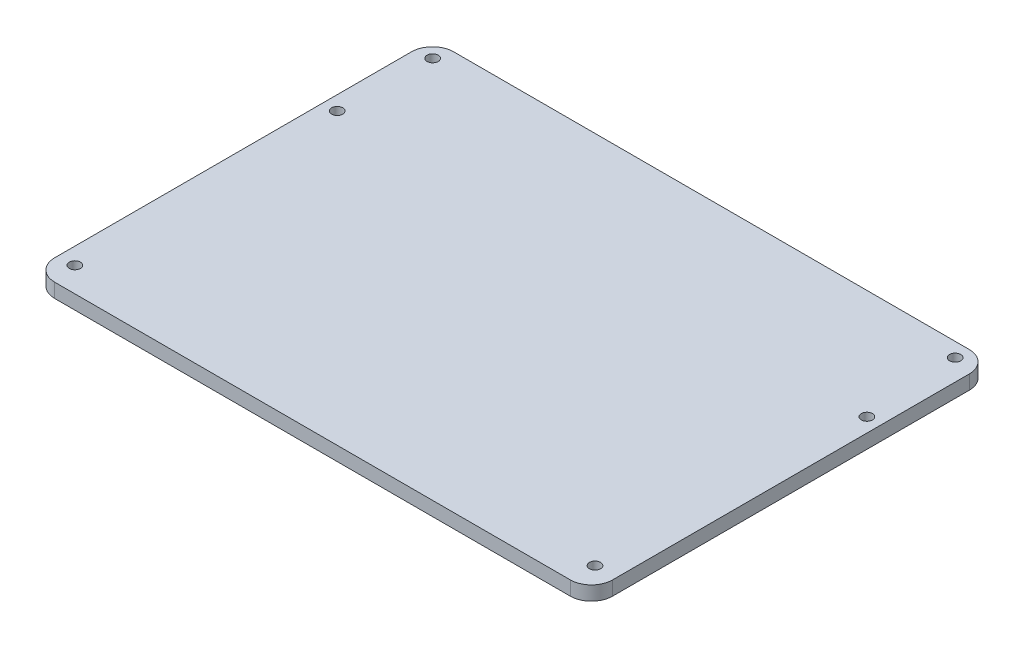
SolidWorks part; units mm, degrees
material "Thornel Mat VMA"
ref_plane "Front Plane" through (0, 0, 0) normal (0, 0, 1) x (1, 0, 0)
ref_plane "Top Plane" through (0, 0, 0) normal (0, 1, 0) x (1, 0, 0)
ref_plane "Right Plane" through (0, 0, 0) normal (1, 0, 0) x (0, 0, -1)
sketch "Sketch1" plane through (0, 0, 0) normal (0, 1, 0) x (1, 0, 0)
  line L0 (-75.9923, 25.544) -> (109.4277, 25.544)
  line L1 (-83.6123, 17.924) -> (-83.6123, -110.346)
  line L2 (117.0477, 17.924) -> (117.0477, -110.346)
  line L3 (-75.9923, -117.966) -> (109.4277, -117.966)
  arc A0 (-83.6123, -110.346) -> (-75.9923, -117.966) centre (-75.9923, -110.346) ccw
  arc A1 (117.0477, -110.346) -> (109.4277, -117.966) centre (109.4277, -110.346) cw
  arc A2 (109.4277, 25.544) -> (117.0477, 17.924) centre (109.4277, 17.924) cw
  arc A3 (-83.6123, 17.924) -> (-75.9923, 25.544) centre (-75.9923, 17.924) cw
  point P7 (-83.6123, -117.966)
  point P12 (117.0477, 25.544)
  point P15 (-83.6123, 25.544)
  dimension "D3" = 7.62
  dimension "D1" = 143.51
  dimension "D2" = 200.66
extrude "Boss-Extrude1" add sketch "Sketch1" along normal blind 5.08
sketch "Sketch2" plane through (0, 5.08, 0) normal (0, 1, 0) x (1, 0, 0)
  line L0 (-83.6123, 17.924) -> (-83.6123, -110.346) construction
  line L1 (-75.9923, -117.966) -> (109.4277, -117.966) construction
  line L2 (117.0477, -110.346) -> (117.0477, 17.924) construction
  line L4 (109.4277, 25.544) -> (-75.9923, 25.544) construction
  line L5 (104.3477, 20.464) -> (-70.9123, 20.464) construction
  line L6 (16.7177, 25.544) -> (16.7177, 87.9955)
  circle A0 centre (-77.6433, -109.076) radius 2
  circle A1 centre (109.4277, -109.076) radius 2
  circle A2 centre (109.4277, 20.464) radius 2
  circle A3 centre (-77.7703, 19.7379) radius 2
  arc A5 (117.0477, 17.924) -> (109.4277, 25.544) centre (109.4277, 17.924) ccw construction
  arc A7 (-75.9923, 25.544) -> (-83.6123, 17.924) centre (-75.9923, 17.924) ccw construction
  circle A8 centre (-78.5323, -13.826) radius 2
  circle A9 centre (-78.5323, -131.936) radius 2
  circle A10 centre (111.9677, -13.826) radius 2
  circle A11 centre (111.9677, -131.936) radius 2
  dimension "D1" = 4
  dimension "D2" = 4
  dimension "D3" = 4
  dimension "D4" = 4
  dimension "D14" = 4
  dimension "D16" = 4
  dimension "D5" = 2.54
  dimension "D6" = 2.54
  dimension "D7" = 5.842
  dimension "D8" = 5.969
  dimension "D9" = 8.89
  dimension "D10" = 8.89
  dimension "D11" = 7.62
  dimension "D12" = 7.62
  dimension "D13" = 5.08
  dimension "D15" = 39.37
  dimension "D17" = 5.08
  dimension "D18" = 152.4
extrude "Cut-Extrude1" cut sketch "Sketch2" against normal through all contours A3 | A8 | A9 | A0 | A1 | A11 | A10 | A2
